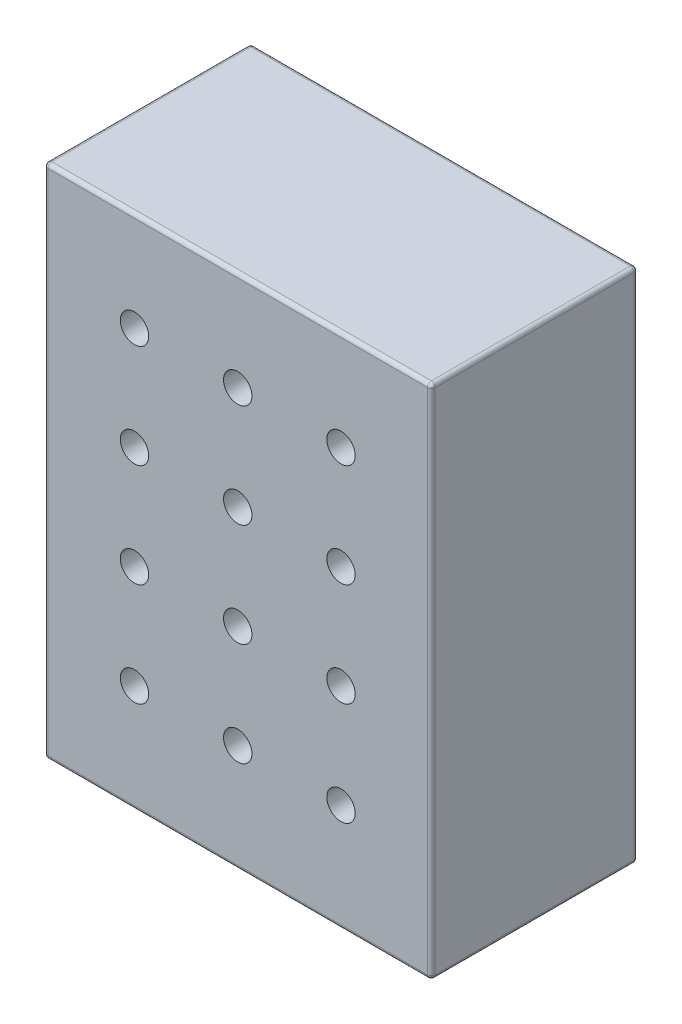
SolidWorks part; units mm, degrees
ref_plane "Front Plane" through (0, 0, 0) normal (0, 0, 1) x (1, 0, 0)
ref_plane "Top Plane" through (0, 0, 0) normal (0, 1, 0) x (1, 0, 0)
ref_plane "Right Plane" through (0, 0, 0) normal (1, 0, 0) x (0, 0, -1)
sketch "Sketch1" plane through (0, 0, 0) normal (0, 0, 1) x (1, 0, 0)
  line L0 (361.6397, 443.5293) -> (661.6397, 443.5293)
  line L1 (661.6397, 443.5293) -> (661.6397, 843.5293)
  line L2 (661.6397, 843.5293) -> (361.6397, 843.5293)
  line L3 (361.6397, 843.5293) -> (361.6397, 443.5293)
  circle B0 centre (431.6397, 526.8072) radius 11
  circle B1 centre (431.6397, 606.8072) radius 11
  circle B2 centre (431.6397, 686.8072) radius 11
  circle B3 centre (431.6397, 766.8072) radius 11
  circle B4 centre (511.6397, 526.8072) radius 11
  circle B5 centre (511.6397, 606.8072) radius 11
  circle B6 centre (511.6397, 686.8072) radius 11
  circle B7 centre (511.6397, 766.8072) radius 11
  circle B8 centre (591.6397, 526.8072) radius 11
  circle B9 centre (591.6397, 606.8072) radius 11
  circle B10 centre (591.6397, 686.8072) radius 11
  circle B11 centre (591.6397, 766.8072) radius 11
sketch_block_instance "*U1-1"
sketch_block "*U1"
extrude "Boss-Extrude1" add sketch "Sketch1" along normal blind 160
fillet "Fillet1" radius 3 12 edges at (511.6397, 843.5293, 0) (661.6397, 843.5293, 80) (661.6397, 643.5293, 0) (661.6397, 443.5293, 80) (511.6397, 443.5293, 0) (511.6397, 443.5293, 160) (361.6397, 443.5293, 80) (361.6397, 643.5293, 0) (661.6397, 643.5293, 160) (361.6397, 843.5293, 80) (511.6397, 843.5293, 160) (361.6397, 643.5293, 160)
